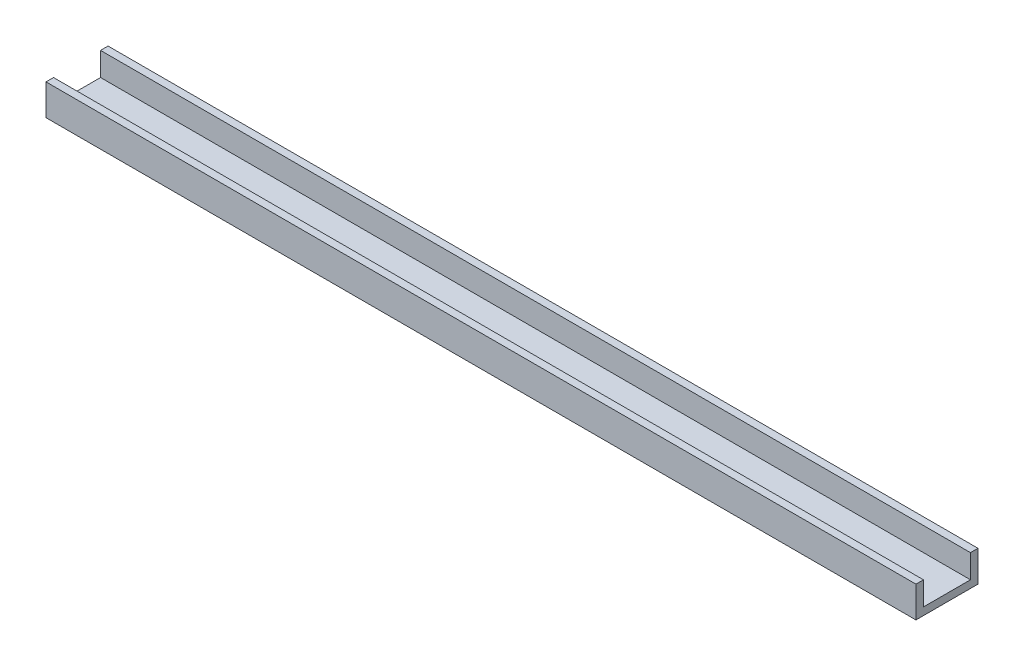
SolidWorks part; units mm, degrees
ref_plane "Ebene vorne" through (0, 0, 0) normal (0, 0, 1) x (1, 0, 0)
ref_plane "Ebene oben" through (0, 0, 0) normal (0, 1, 0) x (1, 0, 0)
ref_plane "Ebene rechts" through (0, 0, 0) normal (1, 0, 0) x (0, 0, -1)
sketch "Skizze1" plane through (0, 0, 0) normal (1, 0, 0) x (0, 0, -1)
  line L0 (0, 50) -> (0, 0)
  line L1 (0, 0) -> (100, 0)
  line L2 (100, 0) -> (100, 50)
  line L3 (-16, 50) -> (-16, -16)
  line L4 (-16, -16) -> (116, -16)
  line L5 (116, -16) -> (116, 50)
  line L6 (0, 50) -> (-16, 50)
  line L7 (100, 50) -> (116, 50)
  dimension "D1" = 100
  dimension "D2" = 50
  dimension "D3" = 50
  dimension "D4" = 16
extrude "Aufsatz-Linear austragen1" add sketch "Skizze1" along normal blind 1850
